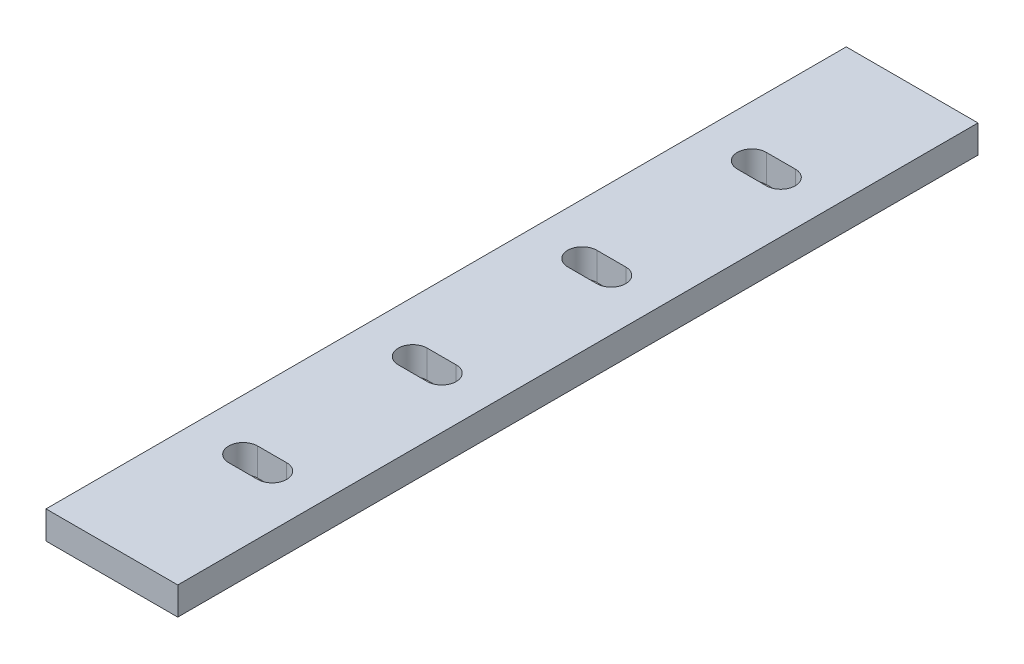
SolidWorks part; units mm, degrees
ref_plane "Front Plane" through (0, 0, 0) normal (0, 0, 1) x (1, 0, 0)
ref_plane "Top Plane" through (0, 0, 0) normal (0, 1, 0) x (1, 0, 0)
ref_plane "Right Plane" through (0, 0, 0) normal (1, 0, 0) x (0, 0, -1)
sketch "Sketch2" plane through (0, 0, 0) normal (0, 1, 0) x (1, 0, 0)
  line L0 (9.15, 16.6) -> (5.85, 16.6) construction
  line L1 (0, 0) -> (15, 0)
  line L2 (0, 0) -> (0, 91.1)
  line L3 (0, 91.1) -> (15, 91.1)
  line L4 (15, 0) -> (15, 91.1)
  line L5 (7.5, 0) -> (7.5, 91.1) construction
  line L6 (9.15, 14.95) -> (5.85, 14.95)
  line L7 (9.15, 18.25) -> (5.85, 18.25)
  line L8 (9.15, 35.9) -> (5.85, 35.9) construction
  line L9 (9.15, 34.25) -> (5.85, 34.25)
  line L10 (9.15, 37.55) -> (5.85, 37.55)
  line L11 (9.15, 55.2) -> (5.85, 55.2) construction
  line L12 (9.15, 53.55) -> (5.85, 53.55)
  line L13 (9.15, 56.85) -> (5.85, 56.85)
  line L14 (9.15, 74.5) -> (5.85, 74.5) construction
  line L15 (9.15, 72.85) -> (5.85, 72.85)
  line L16 (9.15, 76.15) -> (5.85, 76.15)
  arc A0 (9.15, 14.95) -> (9.15, 18.25) centre (9.15, 16.6) ccw
  arc A1 (5.85, 18.25) -> (5.85, 14.95) centre (5.85, 16.6) ccw
  arc A2 (9.15, 34.25) -> (9.15, 37.55) centre (9.15, 35.9) ccw
  arc A3 (5.85, 37.55) -> (5.85, 34.25) centre (5.85, 35.9) ccw
  arc A4 (9.15, 53.55) -> (9.15, 56.85) centre (9.15, 55.2) ccw
  arc A5 (5.85, 56.85) -> (5.85, 53.55) centre (5.85, 55.2) ccw
  arc A6 (9.15, 72.85) -> (9.15, 76.15) centre (9.15, 74.5) ccw
  arc A7 (5.85, 76.15) -> (5.85, 72.85) centre (5.85, 74.5) ccw
  point P9 (7.5, 16.6)
  point P17 (7.5, 35.9)
  point P27 (7.5, 55.2)
  point P36 (7.5, 74.5)
  dimension "D2" = 1.65
  dimension "D1" = 15
  dimension "D3" = 14.95
  dimension "D4" = 19.3
  dimension "D5" = 19.3
  dimension "D6" = 19.3
  dimension "D7" = 3.3
  dimension "D8" = 14.95
extrude "Boss-Extrude1" add sketch "Sketch2" along normal blind 3.175
